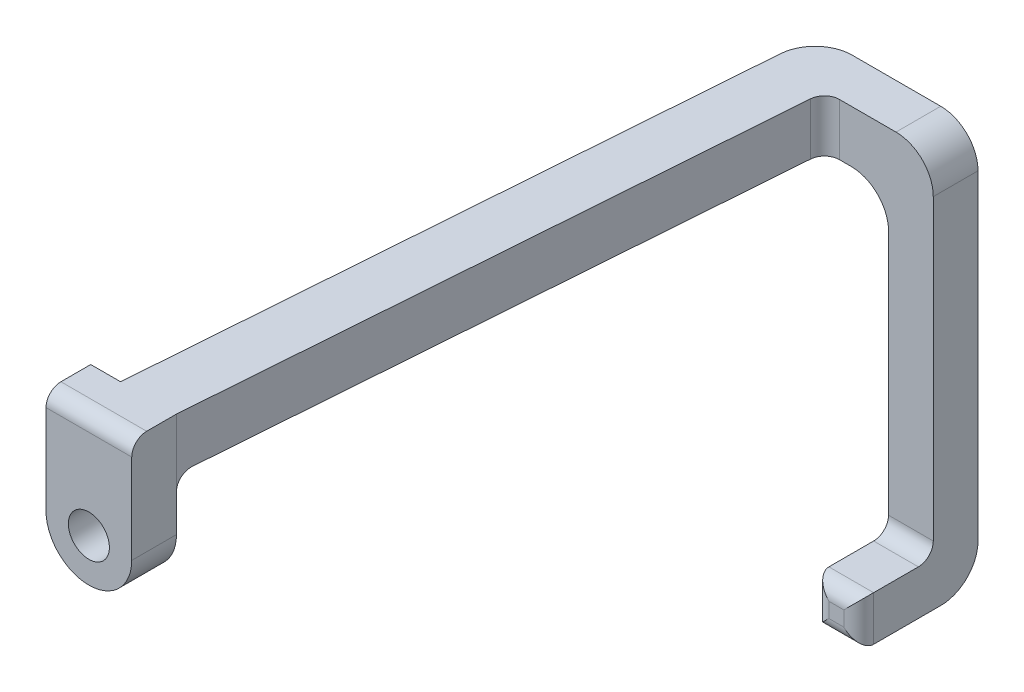
SolidWorks part; units mm, degrees
ref_plane "Front Plane" through (0, 0, 0) normal (1, 0, 0) x (0, 1, 0)
ref_plane "Top Plane" through (0, 0, 0) normal (0, 0, 1) x (0, 1, 0)
ref_plane "Right Plane" through (0, 0, 0) normal (0, 1, 0) x (-1, 0, 0)
sketch "Sketch1" plane through (0, 0, 0) normal (0, 0, 1) x (0, 1, 0)
  line L0 (0, 0) -> (1.375, 0) construction
  line L3 (0, 2.875) -> (7, 2.875)
  line L4 (0, -2.875) -> (7, -2.875)
  line L5 (7, -2.875) -> (7, 2.875)
  arc A0 (0, 2.875) -> (0, -2.875) centre (0, 0) ccw
  circle A3 centre (0, 0) radius 1.375
  point P2 (0, 0)
  dimension "D1" = 2.75
  dimension "D2" = 2.875
  dimension "D3" = 7
extrude "Boss-Extrude1" add sketch "Sketch1" along normal blind 3
sketch "Sketch2" plane through (0, 0, 0) normal (0, 0, -1) x (1, 0, 0)
  line L0 (2.875, -7) -> (-2.875, -7) construction
  line L1 (2.875, -7) -> (-0.875, -7)
  line L4 (2.875, -3.5) -> (2.875, -7)
  line L5 (-0.875, -7) -> (-0.875, -3.5)
  line L6 (-0.875, -3.5) -> (2.875, -3.5)
  line L7 (2.875, 0) -> (2.875, -7) construction
  line L8 (-2.875, -7) -> (-2.875, 0) construction
  dimension "D1" = 2
ref_plane "Plane1" through (0, 0, -43.5) normal (0, 0, -1) x (-1, 0, 0)
sketch "Sketch8" plane through (0, 0, -43.5) normal (0, 0, -1) x (-1, 0, 0)
  line L0 (-2.875, 3.5) -> (-2.875, 7) construction
  line L1 (0.875, 3.5) -> (-2.875, 3.5) construction
  line L2 (0.875, 7) -> (0.875, 3.5) construction
  line L3 (-2.875, 7) -> (0.875, 7) construction
  line L4 (-2.875, 3.5) -> (-2.875, 7) construction
  line L5 (0.875, 3.5) -> (-2.875, 3.5) construction
  line L6 (0.875, 7) -> (0.875, 3.5) construction
  line L7 (-2.875, 7) -> (0.875, 7) construction
  line L8 (-6.125, 3.5) -> (-6.125, 7)
  line L9 (-2.375, 3.5) -> (-2.375, 7)
  line L10 (-6.125, 7) -> (-2.375, 7)
  line L11 (-2.375, 3.5) -> (-6.125, 3.5)
  dimension "D1" = 3.25
loft "Loft1" add profiles "Sketch2", "Sketch8"
sketch "Sketch9" plane through (0, 0, 0) normal (1, 0, 0) x (0, 1, 0)
  line L0 (3.5, 0) -> (3.5, -43.5) construction
  line L1 (7, 0) -> (7, -43.5) construction
  line L2 (3.5, -40.5) -> (3.5, -43.5)
  line L3 (7, -40.5) -> (7, -43.5)
  line L4 (7, -43.5) -> (3.5, -43.5)
  line L6 (7, -40.5) -> (3.5, -40.5)
  dimension "D1" = 3
extrude "Boss-Extrude2" add sketch "Sketch9" along normal blind 7 and the other way up to surface from vertex
sketch "Sketch10" plane through (0, 7, 0) normal (0, 1, 0) x (-1, 0, 0)
  line L7 (-13.125, -43.5) -> (-6.125, -43.5) construction
  line L8 (-5.9009, -40.5) -> (-13.125, -40.5) construction
  line L9 (-13.125, -43.5) -> (-13.125, -40.5) construction
  line L10 (-13.125, -43.5) -> (-10.125, -43.5)
  line L11 (-10.125, -40.5) -> (-13.125, -40.5)
  line L12 (-13.125, -43.5) -> (-13.125, -40.5)
  line L13 (-10.125, -40.5) -> (-10.125, -43.5)
  dimension "D1" = 3
extrude "Boss-Extrude3" add sketch "Sketch10" against normal blind 23 from surface
sketch "Sketch11" plane through (0, 0, -40.5) normal (0, 0, 1) x (1, 0, 0)
  line L1 (10.125, -19.5) -> (10.125, 3.5) construction
  line L8 (10.125, -19.5) -> (13.125, -19.5) construction
  line L9 (13.125, 7) -> (13.125, -19.5) construction
  line L10 (10.125, -19.5) -> (10.125, -16.5)
  line L11 (10.125, -19.5) -> (13.125, -19.5)
  line L12 (13.125, -16.5) -> (13.125, -19.5)
  line L13 (13.125, -16.5) -> (10.125, -16.5)
  dimension "D1" = 3
extrude "Boss-Extrude4" add sketch "Sketch11" along normal blind 5
fillet "Fillet1" radius 2.5 7 edges at (13.125, 7, -42) (11.625, -19.5, -43.5) (10.125, 3.5, -42)
fillet "Fillet2" radius 1 11 edges at (0, 7, 3) (5.9009, 5.25, -40.5) (11.625, -16.5, -40.5) (11.625, -19.5, -35.5) (13.125, -18, -35.5) (11.625, -16.5, -35.5) (10.125, -18, -35.5)
